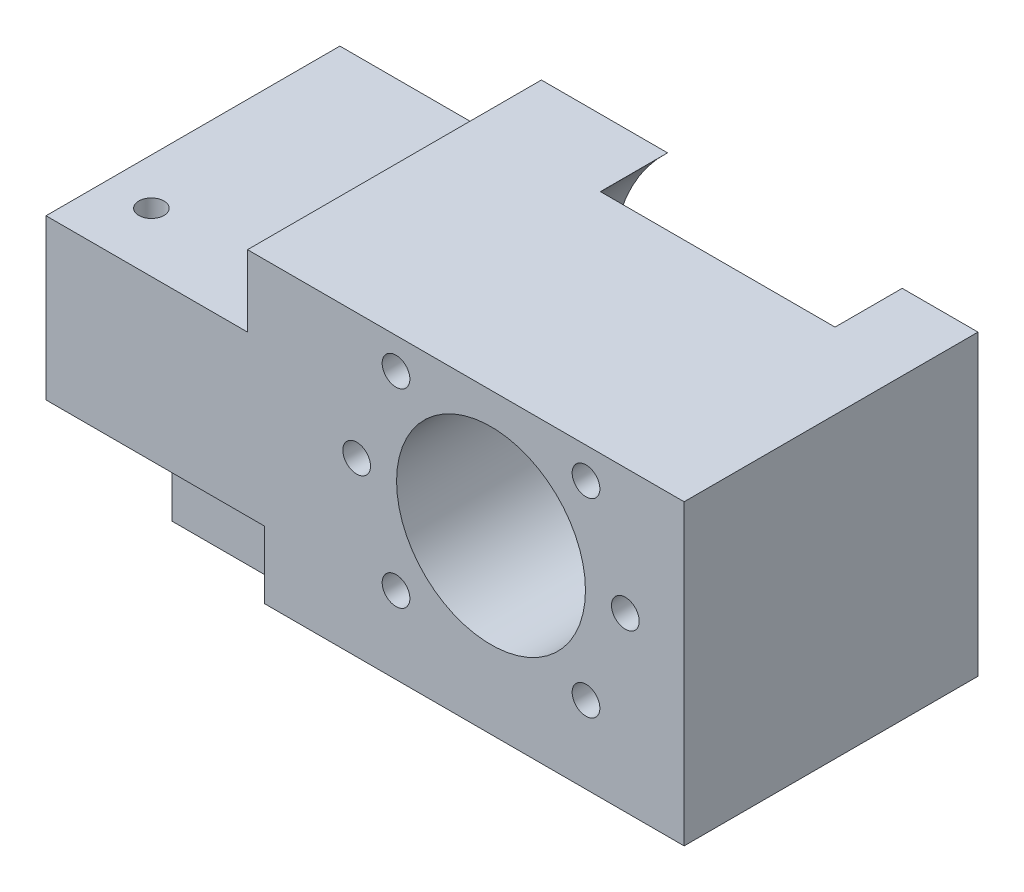
SolidWorks part; units mm, degrees
ref_plane "前视基准面" through (0, 0, 0) normal (0, 0, 1) x (1, 0, 0)
ref_plane "上视基准面" through (0, 0, 0) normal (0, 1, 0) x (1, 0, 0)
ref_plane "右视基准面" through (0, 0, 0) normal (1, 0, 0) x (0, 0, -1)
other "Configuration Table"
sketch "草图1" plane through (0, 0, 0) normal (0, 0, 1) x (1, 0, 0)
  line L1 (-35, -15) -> (35, -15)
  line L2 (-35, -15) -> (-35, 15)
  line L3 (-35, 15) -> (35, 15)
  line L4 (35, -15) -> (35, 15)
  line L5 (0, 15) -> (0, -15) construction
  line L6 (-35, 0) -> (35, 0) construction
  point P0 (0, 0)
  dimension "D1" = 70
  dimension "D2" = 30
extrude "凸台-拉伸1" add sketch "草图1" along normal blind 27
sketch "草图2" plane through (0, 0, 27) normal (0, 0, 1) x (1, 0, 0)
  line L0 (35, -15) -> (35, 15) construction
  line L1 (-35, 15) -> (-35, -15) construction
  line L2 (35, -15) -> (35, 15)
  line L3 (35, 15) -> (28.2288, 15)
  line L6 (-35, -15) -> (35, -15) construction
  line L7 (28.2288, -15) -> (35, -15)
  arc A0 (28.2288, -15) -> (28.2288, 15) centre (15, 0) ccw
  point P8 (-35, 0)
  line M6 (35, -15) -> (35, 15)
  line M7 (35, 15) -> (-35, 15)
  line M9 (-35, -15) -> (35, -15)
  dimension "D1" = 40
extrude "切除-拉伸1" cut sketch "草图2" against normal through all contours A0 M9 M6 | A0 L2 M7
sketch "草图3" plane through (0, 0, 27) normal (0, 0, 1) x (1, 0, 0)
  line L0 (15, 0) -> (31, 0) construction
  line L1 (15, 0) -> (26.3137, 11.3137) construction
  line L2 (15, 0) -> (15, -16) construction
  circle A0 centre (31, 0) radius 1.65
  circle A1 centre (15, 0) radius 16 construction
  circle A2 centre (26.3137, 11.3137) radius 1.65
  circle A3 centre (26.3137, -11.3137) radius 1.65
  circle A4 centre (3.6863, 11.3137) radius 1.65
  circle A5 centre (3.6863, -11.3137) radius 1.65
  circle A6 centre (-1, 0) radius 1.65
  dimension "D1" = 32
  dimension "D3" = 3.3
  dimension "D4" = 3.3
  dimension "D5" = 3.3
  dimension "D2" = 45
extrude "切除-拉伸2" cut sketch "草图3" against normal through all
sketch "草图4" plane through (0, 0, 27) normal (0, 0, 1) x (1, 0, 0)
  line L1 (-35, 15) -> (-14, 15)
  line L2 (-35, 15) -> (-35, 6.5)
  line L3 (-35, 6.5) -> (-14, 6.5)
  line L4 (-14, 15) -> (-14, 6.5)
  dimension "D1" = 8.5
  dimension "D2" = 21
extrude "切除-拉伸3" cut sketch "草图4" against normal through all
sketch "草图7" plane through (0, 0, 0) normal (0, 0, -1) x (-1, 0, 0)
  circle A0 centre (-15, 0) radius 11.25
  dimension "D1" = 22.5
extrude "切除-拉伸5" cut sketch "草图7" against normal through all
sketch "草图8" plane through (0, 0, 0) normal (0, 0, -1) x (-1, 0, 0)
  line L0 (35, -15) -> (-28.2288, -15) construction
  line L1 (35, 6.5) -> (13.5, 6.5)
  line L2 (35, 6.5) -> (35, -15)
  line L3 (35, -15) -> (13.5, -15)
  line L4 (13.5, 6.5) -> (13.5, -15)
extrude "凸台-拉伸2" add sketch "草图8" along normal blind 8
sketch "草图10" plane through (0, -15, 0) normal (0, -1, 0) x (1, 0, 0)
  line L0 (-35, 27) -> (-35, -8) construction
  line L1 (-32.5, 3.95) -> (-17.5, 3.95) construction
  line L2 (-32.5, 3.95) -> (-32.5, 19.95) construction
  line L3 (-32.5, 19.95) -> (-17.5, 19.95) construction
  line L4 (-17.5, 3.95) -> (-17.5, 19.95) construction
  line L5 (-13.5, -8) -> (-35, -8) construction
  circle A0 centre (-32.5, 3.95) radius 1.5 construction
  circle A1 centre (-17.5, 3.95) radius 1.5 construction
  circle A2 centre (-17.5, 19.95) radius 1.5
  circle A3 centre (-32.5, 19.95) radius 1.5
  dimension "D5" = 3
  dimension "D1" = 2.5
  dimension "D2" = 11.95
  dimension "D3" = 16
  dimension "D4" = 15
extrude "切除-拉伸6" cut sketch "草图10" against normal through all
sketch "草图12" plane through (-35, 0, 0) normal (-1, 0, 0) x (0, 0, 1)
  line L4 (27, -15) -> (27, 6.5)
  line L5 (27, 6.5) -> (-8, 6.5)
  line L6 (-8, 6.5) -> (-8, -15)
  line L7 (-8, -15) -> (27, -15)
  line L8 (27, -15) -> (27, 6.5)
  line L9 (27, 6.5) -> (-8, 6.5)
  line L10 (-8, 6.5) -> (-8, -15)
  line L11 (-8, -15) -> (27, -15)
  dimension "D1" = 0
extrude "凸台-拉伸3" add sketch "草图12" along normal blind 3
sketch "草图13" plane through (0, -15, 0) normal (0, -1, 0) x (1, 0, 0)
  circle A1 centre (-32.5, 19.95) radius 3
  circle A2 centre (-17.5, 19.95) radius 3
  dimension "D1" = 6
extrude "切除-拉伸7" cut sketch "草图13" against normal blind 15
sketch "草图14" plane through (0, 0, 27) normal (0, 0, 1) x (1, 0, 0)
  line L1 (28.2288, -15) -> (35, -15)
  line L2 (28.2288, -15) -> (28.2288, -12.9208)
  line L4 (35, -15) -> (35, 0)
  line L5 (28.2288, -9.7067) -> (28.2288, 0)
  line L6 (28.2288, 9.7067) -> (28.2288, 0)
  line L7 (28.2288, 15) -> (35, 15)
  line L8 (28.2288, 15) -> (28.2288, 12.9208)
  line L10 (35, 15) -> (35, 0)
  line L11 (28.2288, 12.9208) -> (28.2288, 9.7067)
  line L12 (28.2288, -12.9208) -> (28.2288, -9.7067)
  arc A0 (28.2288, -15) -> (28.2288, 15) centre (15, 0) ccw construction
  circle A8 centre (31, 0) radius 1.65 construction
  circle A9 centre (31, 0) radius 1.65
  point P13 (29.2023, 15)
  dimension "D1" = 3.2141
  dimension "D2" = 2.0792
  dimension "D3" = 5.2933
  dimension "D4" = 2.0792
  dimension "D5" = 15
extrude "凸台-拉伸4" add sketch "草图14" against normal blind 27
sketch "草图15" plane through (35, 0, 0) normal (1, 0, 0) x (0, 0, -1)
  line L4 (0, -15) -> (0, 15)
  line L5 (0, 15) -> (-27, 15)
  line L6 (-27, 15) -> (-27, -15)
  line L7 (-27, -15) -> (0, -15)
  line L8 (0, -15) -> (0, 15)
  line L9 (0, 15) -> (-27, 15)
  line L10 (-27, 15) -> (-27, -15)
  line L11 (-27, -15) -> (0, -15)
  dimension "D1" = 0
extrude "凸台-拉伸5" add sketch "草图15" along normal blind 3
sketch "草图16" plane through (0, -15, 0) normal (0, -1, 0) x (1, 0, 0)
  line L6 (-13.5, 0) -> (38, 0)
  line L7 (38, 0) -> (38, 27)
  line L8 (38, 27) -> (-38, 27)
  line L9 (-38, 27) -> (-38, -8)
  line L10 (-38, -8) -> (-13.5, -8)
  line L11 (-13.5, -8) -> (-13.5, 0)
  line L12 (-13.5, 0) -> (38, 0)
  line L13 (38, 0) -> (38, 27)
  line L14 (38, 27) -> (-38, 27)
  line L15 (-38, 27) -> (-38, -8)
  line L16 (-38, -8) -> (-13.5, -8)
  line L17 (-13.5, -8) -> (-13.5, 0)
  circle A1 centre (-32.5, 19.95) radius 3 construction
  circle A2 centre (-17.5, 19.95) radius 3 construction
  circle A5 centre (-32.5, 19.95) radius 3
  circle A6 centre (-17.5, 19.95) radius 3
  dimension "D1" = 0
extrude "凸台-拉伸6" add sketch "草图16" along normal blind 5.5
sketch "草图20" plane through (0, 0, 0) normal (0, 0, -1) x (-1, 0, 0)
  line L5 (14, 15) -> (-38, 15)
  line L6 (-38, 15) -> (-38, -20.5)
  line L7 (-38, -20.5) -> (13.5, -20.5)
  line L9 (14, 6.5) -> (14, 15)
  line L10 (14, 15) -> (-38, 15)
  line L11 (-38, 15) -> (-38, -20.5)
  line L14 (14, 6.5) -> (14, 15)
  line L16 (13.5, 6.5) -> (14, 6.5)
  line L17 (13.5, 6.5) -> (14, 6.5)
  line L18 (-38, -20.5) -> (13.5, -20.5)
  line L20 (13.5, -20.5) -> (13.5, 6.5)
  line L21 (13.5, -20.5) -> (13.5, 6.5)
  circle A0 centre (-15, 0) radius 11.25 construction
  circle A1 centre (-15, 0) radius 11.25
  dimension "D1" = 0
sketch "草图22" plane through (0, -20.5, 0) normal (0, -1, 0) x (1, 0, 0)
  line L1 (-38, 27) -> (-12, 27)
  line L2 (-38, 27) -> (-38, 12)
  line L3 (-38, 12) -> (-12, 12)
  line L4 (-12, 27) -> (-12, 12)
  dimension "D1" = 26
  dimension "D2" = 15
extrude "切除-拉伸9" cut sketch "草图22" against normal blind 8
extrude "凸台-拉伸8" add sketch "草图20" along normal blind 8
sketch "草图21" plane through (0, 0, -8) normal (0, 0, -1) x (-1, 0, 0)
  line L0 (-27.816, -16) -> (-2.184, -16)
  line L5 (14, 15) -> (-38, 15) construction
  arc A0 (-2.184, -16) -> (-27.816, -16) centre (-15, 0) ccw
  dimension "D1" = 41
  dimension "D2" = 31
extrude "切除-拉伸8" cut sketch "草图21" against normal blind 8
sketch "草图23" plane through (0, -20.5, 0) normal (0, -1, 0) x (1, 0, 0)
  line L0 (-38, -8) -> (38, -8) construction
  line L1 (-38, 12) -> (-12, 12)
  line L2 (-38, 12) -> (-38, -8)
  line L3 (-38, -8) -> (-12, -8)
  line L4 (-12, 12) -> (-12, -8)
  dimension "D1" = 26
extrude "凸台-拉伸9" add sketch "草图23" along normal blind 17
sketch "草图24" plane through (0, 0, -8) normal (0, 0, -1) x (-1, 0, 0)
  line L0 (12, -20.5) -> (-38, -20.5) construction
  line L2 (12, -37.5) -> (12, -20.5) construction
  circle A0 centre (17, -27) radius 2
  circle A1 centre (25, -27) radius 2
  dimension "D3" = 4
  dimension "D1" = 6.5
  dimension "D2" = 5
  dimension "D4" = 8
extrude "切除-拉伸10" cut sketch "草图24" against normal through all
sketch "草图25" plane through (0, 0, -8) normal (0, 0, -1) x (-1, 0, 0)
  circle A0 centre (17, -27) radius 3.75
  circle A1 centre (25, -27) radius 3.75
  dimension "D1" = 7.5
extrude "切除-拉伸11" cut sketch "草图25" against normal blind 5
sketch "草图26" plane through (0, -37.5, 0) normal (0, -1, 0) x (1, 0, 0)
  line L0 (-12, 12) -> (-38, 12) construction
  line L1 (-38, 12) -> (-38, -8) construction
  circle A0 centre (-31, 7) radius 3.1
  dimension "D1" = 6.2
  dimension "D2" = 5
  dimension "D3" = 7
extrude "切除-拉伸12" cut sketch "草图26" against normal blind 16
sketch "草图27" plane through (0, -21.5, 0) normal (0, -1, 0) x (1, 0, 0)
  circle A0 centre (-31, 7) radius 1.25
  dimension "D1" = 2.5
extrude "切除-拉伸13" cut sketch "草图27" against normal blind 10
sketch "草图28" plane through (0, -37.5, 0) normal (0, -1, 0) x (1, 0, 0)
  line L0 (-38, -8) -> (-12, -8) construction
  line L1 (-32, 4.0657) -> (-30, 4.0657)
  line L2 (-32, 4.0657) -> (-32, -8)
  line L3 (-32, -8) -> (-30, -8)
  line L4 (-30, 4.0657) -> (-30, -8)
  circle A0 centre (-31, 7) radius 3.1 construction
  dimension "D1" = 2
extrude "切除-拉伸14" cut sketch "草图28" against normal blind 16
fillet "圆角1" radius 2 2 edges at (-30, -29.5, 4.0657) (-32, -29.5, 4.0657)
sketch "草图29" plane through (-38, 0, 0) normal (-1, 0, 0) x (0, 0, 1)
  line L0 (-8, 6.5) -> (-8, -37.5) construction
  line L1 (12, -37.5) -> (-8, -37.5)
  line L2 (12, -37.5) -> (12, -32.5)
  line L3 (12, -32.5) -> (-8, -32.5)
  line L4 (-8, -37.5) -> (-8, -32.5)
  dimension "D1" = 5
extrude "切除-拉伸15" cut sketch "草图29" against normal through all
